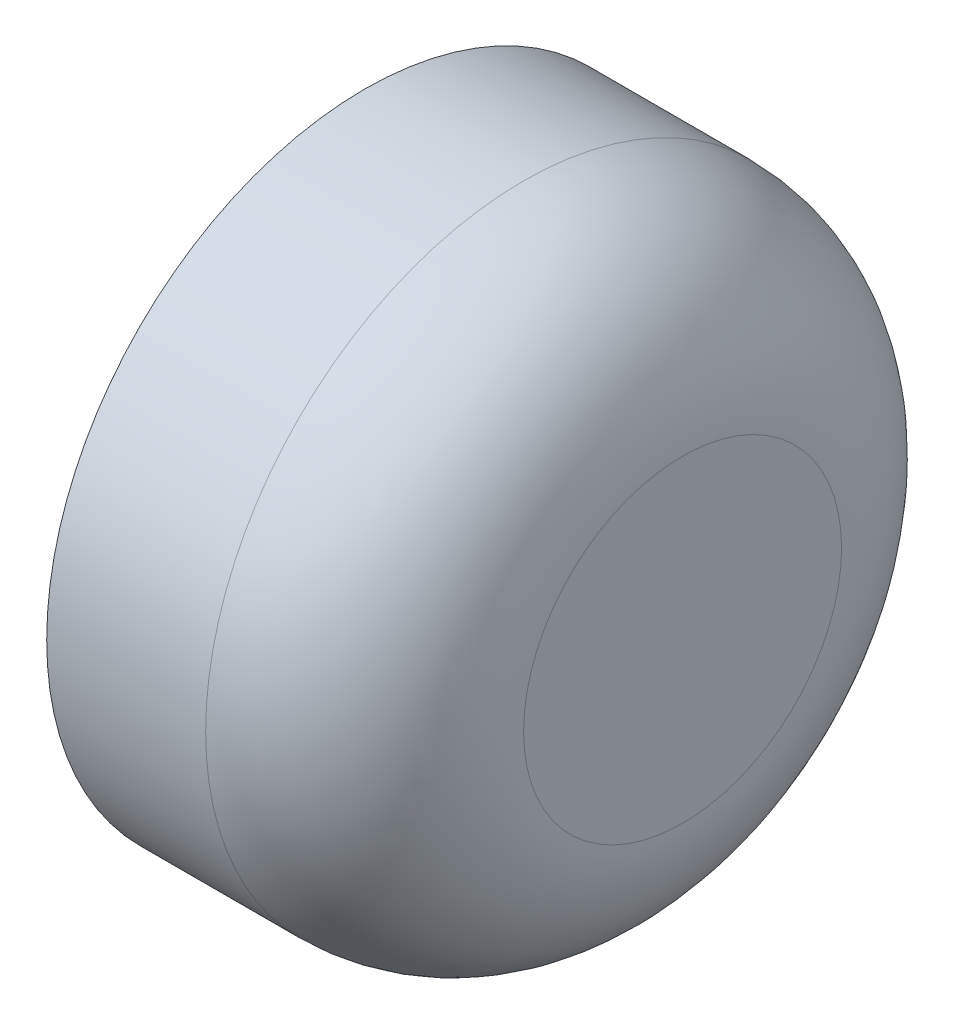
SolidWorks part; units mm, degrees
ref_plane "前视基准面" through (0, 0, 0) normal (0, 0, 1) x (1, 0, 0)
ref_plane "上视基准面" through (0, 0, 0) normal (0, 1, 0) x (1, 0, 0)
ref_plane "右视基准面" through (0, 0, 0) normal (1, 0, 0) x (0, 0, -1)
sketch "草图1" plane through (0, 0, 0) normal (1, 0, 0) x (0, 0, -1)
  circle A0 centre (0, 0) radius 1
extrude "凸台-拉伸1" add sketch "草图1" along normal blind 1
fillet "圆角1" radius 0.5 1 edges at (1, 0, -1)
